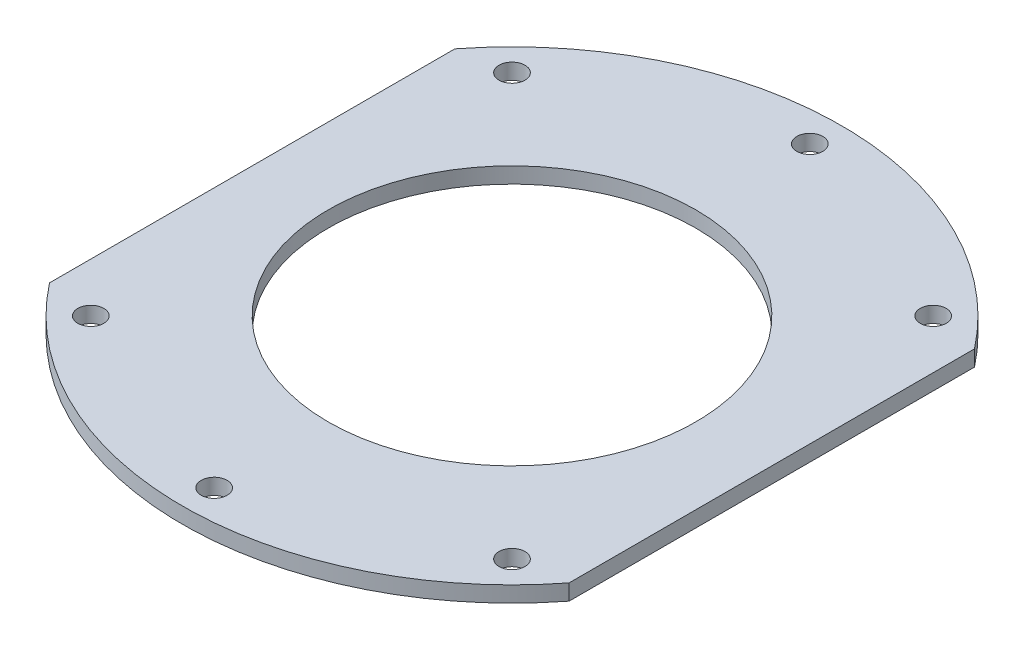
SolidWorks part; units mm, degrees
ref_plane "前视基准面" through (0, 0, 0) normal (0, 0, 1) x (1, 0, 0)
ref_plane "上视基准面" through (0, 0, 0) normal (0, 1, 0) x (1, 0, 0)
ref_plane "右视基准面" through (0, 0, 0) normal (1, 0, 0) x (0, 0, -1)
sketch "草图1" plane through (0, 0, 0) normal (0, 1, 0) x (1, 0, 0)
  circle A0 centre (0, 0) radius 29
  circle A1 centre (0, 0) radius 52
  circle A2 centre (47, 0) radius 2.05
  circle A3 centre (33.234, -33.234) radius 2.05
  circle A4 centre (0, -47) radius 2.05
  circle A5 centre (-33.234, -33.234) radius 2.05
  circle A6 centre (-47, 0) radius 2.05
  circle A7 centre (-33.234, 33.234) radius 2.05
  circle A8 centre (0, 47) radius 2.05
  circle A9 centre (33.234, 33.234) radius 2.05
  circle A10 centre (0, 0) radius 43 construction
  point P6 (52, 0)
  point P9 (43, 0)
  dimension "D1" = 58
  dimension "D2" = 86
  dimension "D3" = 4
  dimension "D4" = 4.1
  dimension "D7" = 5
  dimension "D5" = 8
extrude "凸台-拉伸1" add sketch "草图1" along normal blind 2.5
sketch "草图2" plane through (0, 2.5, 0) normal (0, 1, 0) x (1, 0, 0)
  line L1 (-41, -55.0176) -> (41, -55.0176)
  line L2 (-41, -55.0176) -> (-41, 55.0176)
  line L3 (-41, 55.0176) -> (41, 55.0176)
  line L4 (41, -55.0176) -> (41, 55.0176)
  line L5 (-41, -55.0176) -> (41, 55.0176) construction
  line L6 (-41, 55.0176) -> (41, -55.0176) construction
  point P0 (0, 0)
  dimension "D1" = 82
extrude "切除-拉伸-薄壁1" cut sketch "草图2" against normal blind 4 thin
